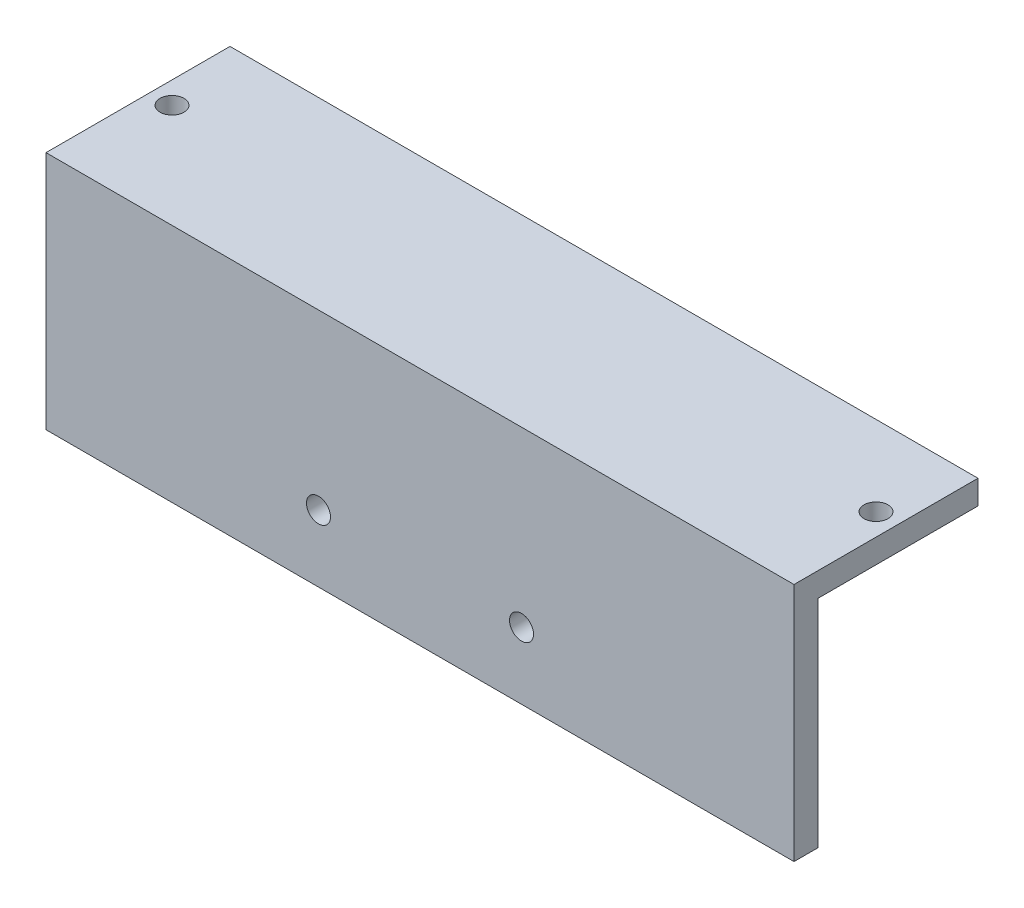
SolidWorks part; units mm, degrees
ref_plane "前视基准面" through (0, 0, 0) normal (0, 0, 1) x (1, 0, 0)
ref_plane "上视基准面" through (0, 0, 0) normal (0, 1, 0) x (1, 0, 0)
ref_plane "右视基准面" through (0, 0, 0) normal (1, 0, 0) x (0, 0, -1)
sketch "草图1" plane through (0, 0, 0) normal (0, 0, 1) x (1, 0, 0)
  line L1 (-18.5965, 11.3158) -> (74.9035, 11.3158)
  line L2 (-18.5965, 11.3158) -> (-18.5965, -18.6842)
  line L3 (-18.5965, -18.6842) -> (74.9035, -18.6842)
  line L4 (74.9035, 11.3158) -> (74.9035, -18.6842)
  dimension "D1" = 93.5
  dimension "D2" = 30
extrude "凸台-拉伸1" add sketch "草图1" along normal blind 3
sketch "草图2" plane through (0, 0, 0) normal (0, 0, -1) x (-1, 0, 0)
  line L0 (-74.9035, -18.6842) -> (-74.9035, 11.3158) construction
  line L1 (18.5965, 11.3158) -> (-74.9035, 11.3158)
  line L2 (18.5965, 11.3158) -> (18.5965, 8.3158)
  line L3 (18.5965, 8.3158) -> (-74.9035, 8.3158)
  line L4 (-74.9035, 11.3158) -> (-74.9035, 8.3158)
  dimension "D1" = 3
extrude "凸台-拉伸2" add sketch "草图2" along normal blind 20
sketch "草图3" plane through (0, 8.3158, 0) normal (0, -1, 0) x (1, 0, 0)
  line L0 (28.1535, 0) -> (28.1535, -20) construction
  line L1 (-18.5965, 0) -> (74.9035, 0) construction
  line L2 (74.9035, -20) -> (-18.5965, -20) construction
  circle A0 centre (-15.8465, -10) radius 1.5
  circle A1 centre (72.1535, -10) radius 1.5
  point P10 (54.4794, -10)
  dimension "D1" = 3
  dimension "D2" = 88
extrude "切除-拉伸1" cut sketch "草图3" against normal blind 20
sketch "草图4" plane through (0, 0, 0) normal (0, 0, -1) x (-1, 0, 0)
  line L0 (-28.1535, 8.3158) -> (-28.1535, -18.6842) construction
  line L1 (-74.9035, 8.3158) -> (18.5965, 8.3158) construction
  line L2 (18.5965, -18.6842) -> (-74.9035, -18.6842) construction
  circle A0 centre (-40.8435, -10.3435) radius 1.5
  circle A1 centre (-15.4635, -10.3435) radius 1.5
  point P10 (-15.4482, -10.3435)
  dimension "D1" = 3
  dimension "D2" = 25.38
extrude "切除-拉伸2" cut sketch "草图4" against normal blind 20
